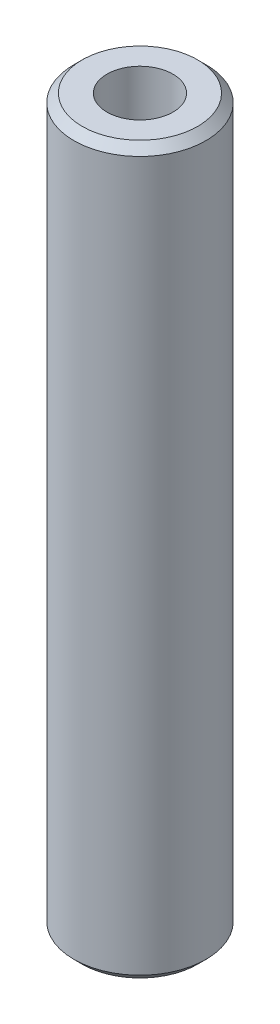
SolidWorks part; units mm, degrees
ref_plane "Front Plane" through (0, 0, 0) normal (0, 0, 1) x (1, 0, 0)
ref_plane "Top Plane" through (0, 0, 0) normal (0, 1, 0) x (1, 0, 0)
ref_plane "Right Plane" through (0, 0, 0) normal (1, 0, 0) x (0, 0, -1)
sketch "Sketch1" plane through (0, 0, 0) normal (0, 1, 0) x (1, 0, 0)
  circle A1 centre (0, 0) radius 2
  circle A2 centre (0, 0) radius 4
  dimension "D1" = 4
  dimension "D2" = 2
extrude "Boss-Extrude1" add sketch "Sketch1" along normal blind 44
chamfer "Chamfer1" distance 0.5 angle 45 2 edges at (0, 0, 4) (0, 44, 4)
